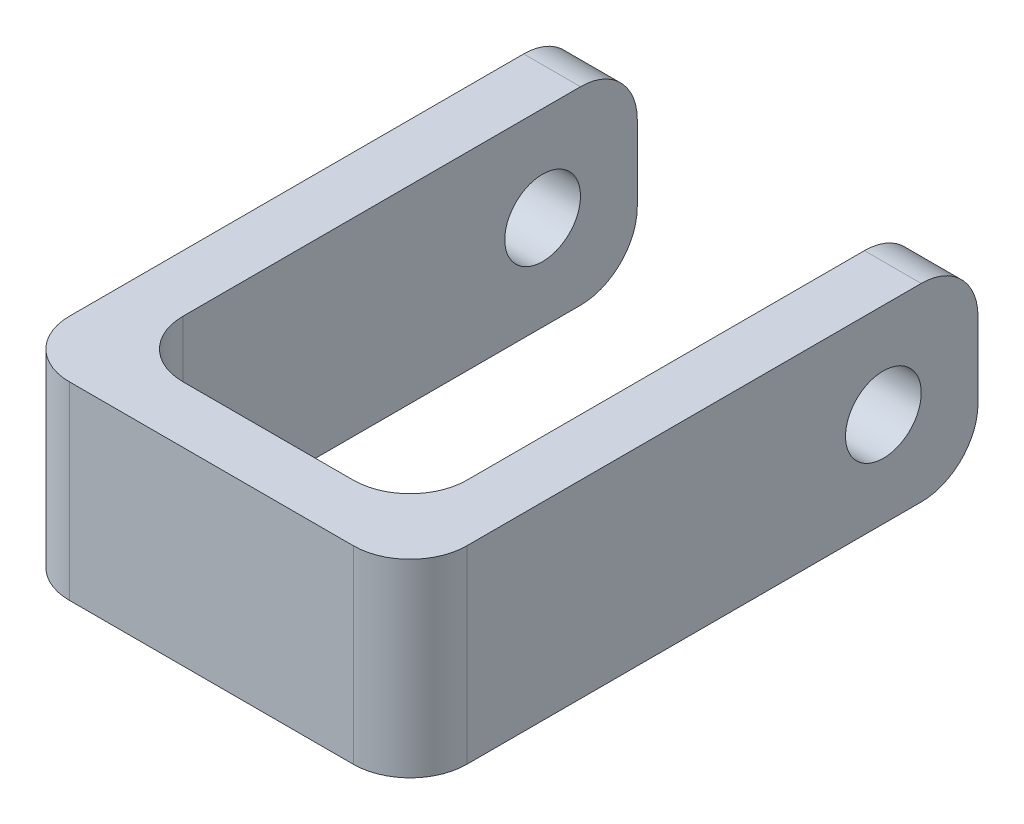
SolidWorks part; units mm, degrees
ref_plane "前视基准面" through (0, 0, 0) normal (0, 0, 1) x (1, 0, 0)
ref_plane "上视基准面" through (0, 0, 0) normal (0, 1, 0) x (1, 0, 0)
ref_plane "右视基准面" through (0, 0, 0) normal (1, 0, 0) x (0, 0, -1)
sketch "草图1" plane through (0, 0, 0) normal (0, 0, 1) x (1, 0, 0)
  line L1 (21, 10) -> (-21, 10)
  line L2 (21, 10) -> (21, -10)
  line L3 (21, -10) -> (-21, -10)
  line L4 (-21, 10) -> (-21, -10)
  line L5 (21, 10) -> (-21, -10) construction
  line L6 (21, -10) -> (-21, 10) construction
  point P0 (0, 0)
extrude "凸台-拉伸1" add sketch "草图1" against normal blind 60
sketch "草图3" plane through (0, -10, 0) normal (0, -1, 0) x (1, 0, 0)
  line L0 (-21, -60) -> (21, -60) construction
  line L1 (-15, -60) -> (15, -60)
  line L2 (-15, -60) -> (-15, -6)
  line L3 (-15, -6) -> (15, -6)
  line L4 (15, -60) -> (15, -6)
extrude "切除-拉伸1" cut sketch "草图3" against normal through all
fillet "圆角1" radius 6 8 edges at (-21, 0, 0) (21, 0, 0) (15, 0, -6) (-15, 0, -6) (-18, 10, -60) (18, 10, -60) (-18, -10, -60) (18, -10, -60)
sketch "草图4" plane through (21, 0, 0) normal (1, 0, 0) x (0, 0, -1)
  circle A0 centre (50, 0) radius 4
extrude "切除-拉伸2" cut sketch "草图4" against normal through all
